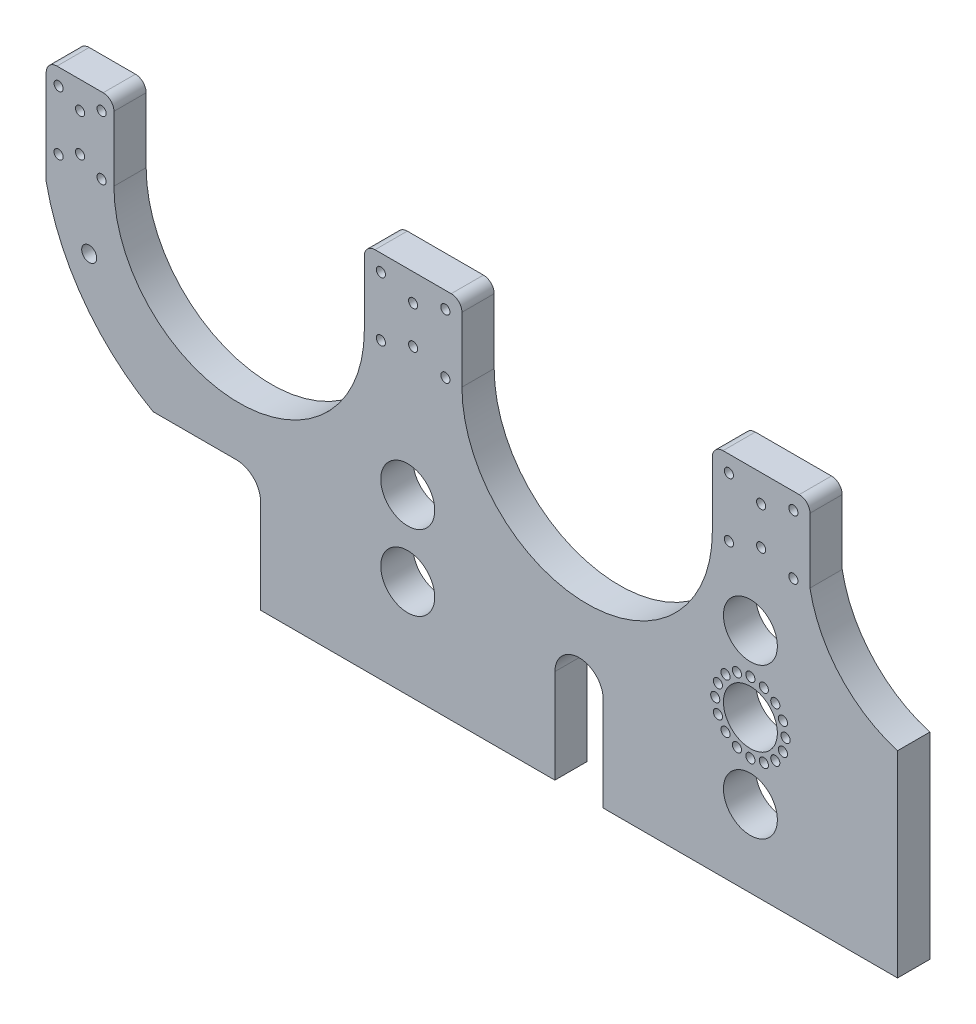
SolidWorks part; units mm, degrees
ref_plane "Front Plane" through (0, 0, 0) normal (0, 0, 1) x (1, 0, 0)
ref_plane "Top Plane" through (0, 0, 0) normal (0, 1, 0) x (1, 0, 0)
ref_plane "Right Plane" through (0, 0, 0) normal (1, 0, 0) x (0, 0, -1)
sketch "Sketch1" plane through (0, 0, 0) normal (0, 0, 1) x (1, 0, 0)
  line L0 (0, 0) -> (273.87, 0)
  line L1 (273.87, 0) -> (273.87, 87.5)
  line L2 (318.87, 87.5) -> (318.87, 0)
  line L3 (318.87, 0) -> (592.74, 0)
  line L4 (592.74, 0) -> (592.74, 183.19)
  line L5 (420.37, 343.8213) -> (511.24, 343.8213)
  line L6 (511.24, 343.8213) -> (511.24, 273.49)
  line L7 (420.37, 343.8213) -> (420.37, 273.49)
  line L8 (318.87, 87.5) -> (273.87, 87.5) construction
  line L9 (0, 0) -> (0, 87.5)
  line L10 (-22.5, 110) -> (-100, 110)
  line L11 (-199.5, 245.6503) -> (-199.5, 343.8213)
  line L12 (-199.5, 343.8213) -> (-136.5, 343.8213)
  line L13 (-136.5, 343.8213) -> (-136.5, 273.49)
  line L14 (96.5, 273.49) -> (96.5, 343.8213)
  line L15 (96.5, 343.8213) -> (187.37, 343.8213)
  line L16 (187.37, 343.8213) -> (187.37, 273.49)
  line L17 (420.37, 273.49) -> (187.37, 273.49) construction
  line L18 (-136.5, 273.49) -> (96.5, 273.49) construction
  line L19 (141.935, 343.8213) -> (141.935, 283.49) construction
  line L20 (-168, 343.8213) -> (-168, 283.49) construction
  line L21 (465.805, 343.8213) -> (465.805, 283.49) construction
  line L22 (-188, 328.49) -> (-188, 273.49) construction
  line L23 (-188, 300.99) -> (-136.5, 300.99) construction
  line L24 (171.935, 328.49) -> (171.935, 273.49) construction
  line L25 (171.935, 300.99) -> (96.5, 300.99) construction
  line L26 (495.805, 328.49) -> (495.805, 273.49) construction
  line L27 (495.805, 300.99) -> (420.37, 300.99) construction
  line L28 (455.81, 211.5) -> (455.81, 71.5) construction
  line L29 (455.81, 141.5) -> (455.81, 174.25) construction
  line L30 (455.81, 141.5) -> (468.3429, 171.7571) construction
  arc A1 (273.87, 87.5) -> (318.87, 87.5) centre (296.37, 87.5) cw
  arc A2 (0, 87.5) -> (-22.5, 110) centre (-22.5, 87.5) ccw
  arc A3 (187.37, 273.49) -> (420.37, 273.49) centre (303.87, 273.49) ccw
  arc A4 (-136.5, 273.49) -> (96.5, 273.49) centre (-20, 273.49) ccw
  circle A5 centre (455.81, 71.5) radius 25.1
  circle A6 centre (455.81, 211.5) radius 25.1
  arc A10 (511.24, 273.49) -> (592.74, 183.19) centre (625.753, 294.9146) ccw
  circle A11 centre (136.93, 91.5) radius 25.1
  circle A12 centre (136.93, 161.5) radius 25.1
  circle A13 centre (-188, 328.49) radius 4.25
  circle A14 centre (-188, 273.49) radius 4.25
  circle A15 centre (-148, 328.49) radius 4.25
  circle A16 centre (-148, 273.49) radius 4.25
  circle A19 centre (111.935, 328.49) radius 4.25
  circle A20 centre (171.935, 328.49) radius 4.25
  circle A21 centre (171.935, 273.49) radius 4.25
  circle A22 centre (111.935, 273.49) radius 4.25
  circle A25 centre (495.805, 328.49) radius 4.25
  circle A26 centre (435.805, 328.49) radius 4.25
  circle A27 centre (495.805, 273.49) radius 4.25
  circle A30 centre (435.805, 273.49) radius 4.25
  circle A33 centre (-159.5, 207.5) radius 7
  circle A34 centre (-168, 318.49) radius 4.25
  circle A35 centre (-168, 283.49) radius 4.25
  circle A36 centre (141.935, 318.49) radius 4.25
  circle A37 centre (141.935, 283.49) radius 4.25
  circle A38 centre (465.805, 283.49) radius 4.25
  circle A39 centre (465.805, 318.49) radius 4.25
  circle A40 centre (455.81, 141.5) radius 25.1
  circle A41 centre (455.81, 141.5) radius 32.75 construction
  circle A42 centre (455.81, 174.25) radius 4.25
  circle A43 centre (468.3429, 171.7571) radius 4.25
  circle A44 centre (478.9677, 164.6577) radius 4.25
  circle A45 centre (486.0671, 154.0329) radius 4.25
  circle A46 centre (488.56, 141.5) radius 4.25
  circle A47 centre (486.0671, 128.9671) radius 4.25
  circle A48 centre (478.9677, 118.3423) radius 4.25
  circle A49 centre (468.3429, 111.2429) radius 4.25
  circle A50 centre (455.81, 108.75) radius 4.25
  circle A51 centre (443.2771, 111.2429) radius 4.25
  circle A52 centre (432.6523, 118.3423) radius 4.25
  circle A53 centre (425.5529, 128.9671) radius 4.25
  circle A54 centre (423.06, 141.5) radius 4.25
  circle A55 centre (425.5529, 154.0329) radius 4.25
  circle A56 centre (432.6523, 164.6577) radius 4.25
  circle A57 centre (443.2771, 171.7571) radius 4.25
  arc A60 (-199.5, 245.6503) -> (-100, 110) centre (-1.7515, 286.3826) ccw
  point P29 (296.37, 110)
  dimension "D2" = 45
  dimension "D8" = 22.5
  dimension "D10" = 63
  dimension "D13" = 116.5
  dimension "D15" = 50.2
  dimension "D19" = 40
  dimension "D26" = 8.5
  dimension "D27" = 17.5
  dimension "D28" = 14
  dimension "D25" = 30
  dimension "D33" = 1.7515
  dimension "D35" = 30
  dimension "D36" = 65.5
  dimension "D37" = 16
  dimension "D39" = 201.9
  dimension "D40" = 343.8213
  dimension "D1" = 183.19
  dimension "D3" = 273.87
  dimension "D4" = 136.94
  dimension "D5" = 71.5
  dimension "D6" = 140
  dimension "D7" = 110
  dimension "D9" = 100
  dimension "D11" = 90.87
  dimension "D12" = 792.24
  dimension "D14" = 87.5
  dimension "D16" = 136.94
  dimension "D17" = 91.5
  dimension "D18" = 161.5
  dimension "D20" = 20
  dimension "D21" = 17.5
  dimension "D22" = 55
  dimension "D23" = 30
  dimension "D24" = 17.5
  dimension "D29" = 40
  dimension "D30" = 97.5
  dimension "D31" = 65.99
  dimension "D32" = 30
  dimension "D34" = 17.5
  dimension "D38" = 22.5
extrude "Boss-Extrude1" add sketch "Sketch1" along normal blind 30
fillet "Fillet1" radius 10 6 edges at (-136.5, 343.8213, 15) (-199.5, 343.8213, 15) (187.37, 343.8213, 15) (96.5, 343.8213, 15) (420.37, 343.8213, 15) (511.24, 343.8213, 15)
